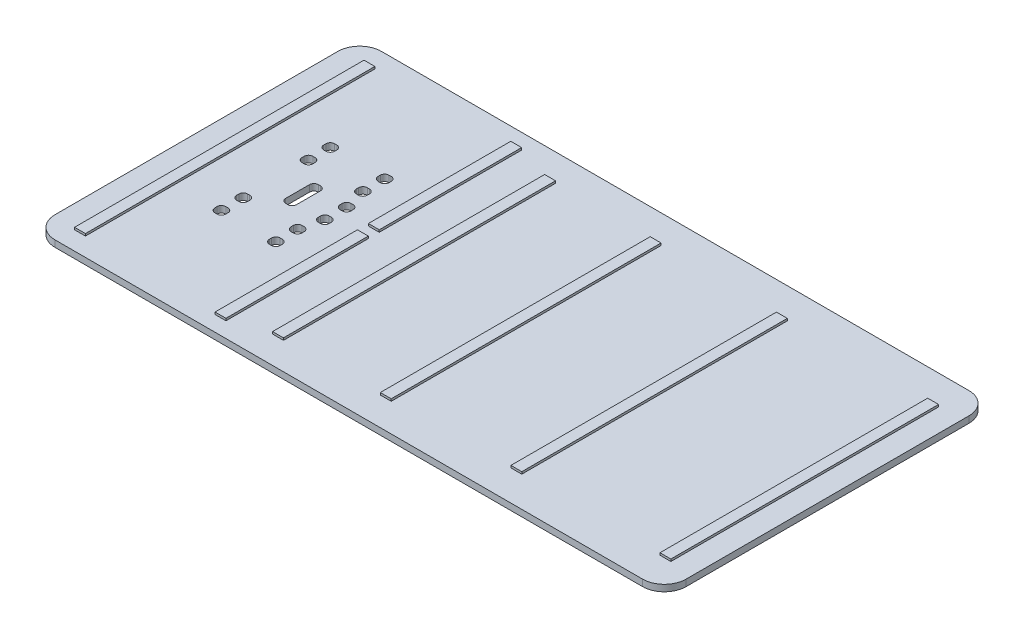
SolidWorks part; units mm, degrees
ref_plane "Front Plane" through (0, 0, 0) normal (0, 0, 1) x (1, 0, 0)
ref_plane "Top Plane" through (0, 0, 0) normal (0, 1, 0) x (1, 0, 0)
ref_plane "Right Plane" through (0, 0, 0) normal (1, 0, 0) x (0, 0, -1)
sketch "Sketch2" plane through (0, 0, 0) normal (0, 1, 0) x (1, 0, 0)
  line L0 (0, 0) -> (28541.0061, 0) construction
  line L1 (-66, 6.8479) -> (-66, -28534.1581) construction
  line L2 (-134.5, 66.5) -> (-129.5, 66.5)
  line L3 (-134.5, 66.5) -> (-134.5, -66.5)
  line L4 (-134.5, -66.5) -> (-129.5, -66.5)
  line L5 (-129.5, 66.5) -> (-129.5, -66.5)
  line L6 (-134.5, 66.5) -> (-129.5, -66.5) construction
  line L7 (-134.5, -66.5) -> (-129.5, 66.5) construction
  line L8 (-68.5, -67.935) -> (-63.5, -2.5) construction
  line L9 (-68.5, 67.935) -> (-63.5, 67.935)
  line L10 (-68.5, 67.935) -> (-68.5, 2.5)
  line L11 (-68.5, 2.5) -> (-63.5, 2.5)
  line L12 (-63.5, 67.935) -> (-63.5, 2.5)
  line L13 (-68.5, 67.935) -> (-63.5, 2.5) construction
  line L14 (-68.5, 2.5) -> (-63.5, 67.935) construction
  line L15 (-68.5, -2.5) -> (-63.5, -67.935) construction
  line L16 (-68.5, -67.935) -> (-68.5, -2.5)
  line L17 (-68.5, -2.5) -> (-63.5, -2.5)
  line L18 (-63.5, -67.935) -> (-63.5, -2.5)
  line L19 (-68.5, -67.935) -> (-63.5, -67.935)
  line L20 (-132, 0) -> (-132, -50000) construction
  line L21 (-47.5, 62.5) -> (-42.5, 62.5)
  line L22 (-47.5, 62.5) -> (-47.5, -62.5)
  line L23 (-47.5, -62.5) -> (-42.5, -62.5)
  line L24 (-42.5, 62.5) -> (-42.5, -62.5)
  line L25 (-47.5, 62.5) -> (-42.5, -62.5) construction
  line L26 (-47.5, -62.5) -> (-42.5, 62.5) construction
  line L27 (1.5, 62) -> (6.5, 62)
  line L28 (1.5, 62) -> (1.5, -62)
  line L29 (1.5, -62) -> (6.5, -62)
  line L30 (6.5, 62) -> (6.5, -62)
  line L31 (1.5, 62) -> (6.5, -62) construction
  line L32 (1.5, -62) -> (6.5, 62) construction
  line L33 (129.5, 61.5) -> (134.5, 61.5)
  line L34 (129.5, 61.5) -> (129.5, -61.5)
  line L35 (129.5, -61.5) -> (134.5, -61.5)
  line L36 (134.5, 61.5) -> (134.5, -61.5)
  line L37 (129.5, 61.5) -> (134.5, -61.5) construction
  line L38 (129.5, -61.5) -> (134.5, 61.5) construction
  line L39 (60.5, 61) -> (65.5, 61)
  line L40 (60.5, 61) -> (60.5, -61)
  line L41 (60.5, -61) -> (65.5, -61)
  line L42 (65.5, 61) -> (65.5, -61)
  line L43 (60.5, 61) -> (65.5, -61) construction
  line L44 (60.5, -61) -> (65.5, 61) construction
  line L45 (-45, 0) -> (-45, -50000) construction
  line L46 (4, 0) -> (4, -50000) construction
  line L47 (132, 0) -> (132, -50000) construction
  line L48 (63, 0) -> (63, -50000) construction
  line L49 (-132, 66.5) -> (132, 66.5) construction
  line L50 (0, 0) -> (0, -50000) construction
  point P3 (-132, 0)
  point P10 (-66, 35.2175)
  point P19 (-45, 0)
  point P24 (4, 0)
  point P29 (132, 0)
  point P34 (63, 0)
  dimension "D14" = 132
extrude "ElementGeometry" add sketch "Sketch2" along normal blind 1 from surface at 0 starting at plane "Top Plane"
sketch "Sketch5" plane through (0, 0, 0) normal (0, 1, 0) x (1, 0, 0)
  line L1 (-145, 75) -> (145, 75)
  line L2 (-145, 75) -> (-145, -75)
  line L3 (-145, -75) -> (145, -75)
  line L4 (145, 75) -> (145, -75)
  line L5 (-145, 75) -> (145, -75) construction
  line L6 (-145, -75) -> (145, 75) construction
  point P0 (0, 0)
  dimension "D1" = 290
  dimension "D2" = 150
extrude "BoardGeometry" add sketch "Sketch5" against normal blind 3 from surface at 0 starting at plane "Top Plane"
sketch "Sketch7" plane through (0, 0, 0) normal (0, 1, 0) x (1, 0, 0)
  line L0 (0, 0) -> (-50000, 0) construction
  line L1 (-81, 5) -> (-81, -5) construction
  line L2 (-83.5, 2.5) -> (-78.5, 7.5) construction
  line L3 (-83.5, -2.5) -> (-78.5, -2.5)
  line L4 (-83.5, -2.5) -> (-83.5, -7.5)
  line L5 (-83.5, -7.5) -> (-78.5, -7.5)
  line L6 (-78.5, -2.5) -> (-78.5, -7.5)
  line L7 (-83.5, -2.5) -> (-78.5, -7.5) construction
  line L8 (-83.5, -7.5) -> (-78.5, -2.5) construction
  line L9 (-83.5, 7.5) -> (-78.5, 2.5) construction
  line L10 (-83.5, 2.5) -> (-83.5, 7.5)
  line L11 (-83.5, 7.5) -> (-78.5, 7.5)
  line L12 (-78.5, 2.5) -> (-78.5, 7.5)
  line L13 (-83.5, 2.5) -> (-78.5, 2.5)
  line L14 (-66, 2.5) -> (-66, -2.5) construction
  line L15 (-63.5, 2.5) -> (-68.5, 2.5) construction
  line L16 (-68.5, -2.5) -> (-63.5, -2.5) construction
  line L17 (-68.5, -67.935) -> (-68.5, -2.5) construction
  line L19 (-98.5, 7.5) -> (-93.5, 7.5)
  line L20 (-98.5, 7.5) -> (-98.5, -7.5)
  line L21 (-98.5, -7.5) -> (-93.5, -7.5)
  line L22 (-93.5, 7.5) -> (-93.5, -7.5)
  line L23 (-98.5, 7.5) -> (-93.5, -7.5) construction
  line L24 (-98.5, -7.5) -> (-93.5, 7.5) construction
  point P3 (-66, 0)
  point P14 (-81, 0)
  point P24 (-96, 0)
  dimension "D1" = 5
  dimension "D2" = 5
  dimension "D3" = 5
  dimension "D4" = 10
  dimension "D5" = 10
extrude "CableCutout" cut sketch "Sketch7" against normal up to next
sketch "Sketch8" plane through (0, 0, 0) normal (0, 1, 0) x (1, 0, 0)
  line L0 (-98.5, 7.5) -> (-93.5, -7.5) construction
  line L1 (-93.5, 7.5) -> (-98.5, -7.5) construction
  line L2 (-93.5, 7.5) -> (-98.5, 7.5) construction
  line L3 (-98.5, -7.5) -> (-93.5, -7.5) construction
  line L4 (-98.5, 7.5) -> (-98.5, -7.5) construction
  line L5 (-93.5, -7.5) -> (-93.5, 7.5) construction
  line L6 (-96, -2.0682) -> (-96, -50002.0682) construction
  line L7 (-108.5, 15) -> (-83.5, 15) construction
  line L8 (-111, 17.5) -> (-106, 17.5)
  line L9 (-111, 17.5) -> (-111, 12.5)
  line L10 (-111, 12.5) -> (-106, 12.5)
  line L11 (-106, 17.5) -> (-106, 12.5)
  line L12 (-111, 17.5) -> (-106, 12.5) construction
  line L13 (-111, 12.5) -> (-106, 17.5) construction
  line L14 (0, 0) -> (50000, 0) construction
  line L15 (-81, 17.5) -> (-86, 12.5) construction
  line L16 (-81, 12.5) -> (-86, 17.5) construction
  line L17 (-81, 17.5) -> (-81, 12.5)
  line L18 (-81, 12.5) -> (-86, 12.5)
  line L19 (-86, 17.5) -> (-86, 12.5)
  line L20 (-81, 17.5) -> (-86, 17.5)
  line L21 (-81, -12.5) -> (-86, -17.5) construction
  line L22 (-81, -17.5) -> (-86, -12.5) construction
  line L23 (-111, -12.5) -> (-106, -17.5) construction
  line L24 (-108.5, -15) -> (-83.5, -15) construction
  line L25 (-81, -17.5) -> (-81, -12.5)
  line L26 (-81, -12.5) -> (-86, -12.5)
  line L27 (-86, -17.5) -> (-86, -12.5)
  line L28 (-81, -17.5) -> (-86, -17.5)
  line L29 (-111, -17.5) -> (-111, -12.5)
  line L30 (-111, -12.5) -> (-106, -12.5)
  line L31 (-106, -17.5) -> (-106, -12.5)
  line L32 (-111, -17.5) -> (-106, -17.5)
  line L33 (-106, -12.5) -> (-111, -17.5) construction
  line L34 (-108.5, -15) -> (-108.5, -25) construction
  line L35 (-108.5, -25) -> (-83.5, -25) construction
  line L36 (-83.5, -25) -> (-83.5, -15) construction
  line L37 (-81, -27.5) -> (-86, -27.5)
  line L38 (-111, -22.5) -> (-106, -22.5)
  line L39 (-111, -22.5) -> (-111, -27.5)
  line L40 (-111, -27.5) -> (-106, -27.5)
  line L41 (-106, -22.5) -> (-106, -27.5)
  line L42 (-111, -22.5) -> (-106, -27.5) construction
  line L43 (-111, -27.5) -> (-106, -22.5) construction
  line L44 (-81, -22.5) -> (-81, -27.5)
  line L45 (-81, -27.5) -> (-86, -22.5) construction
  line L46 (-81, -22.5) -> (-86, -27.5) construction
  line L47 (-86, -22.5) -> (-86, -27.5)
  line L48 (-81, -22.5) -> (-86, -22.5)
  line L49 (-81, 27.5) -> (-86, 27.5)
  line L50 (-81, 22.5) -> (-81, 27.5)
  line L51 (-81, 27.5) -> (-86, 22.5) construction
  line L52 (-81, 22.5) -> (-86, 27.5) construction
  line L53 (-86, 22.5) -> (-86, 27.5)
  line L54 (-81, 22.5) -> (-86, 22.5)
  line L55 (-108.5, 25) -> (-83.5, 25) construction
  line L56 (-111, 22.5) -> (-106, 27.5) construction
  line L57 (-111, 27.5) -> (-106, 22.5) construction
  line L58 (-106, 22.5) -> (-106, 27.5)
  line L59 (-111, 27.5) -> (-106, 27.5)
  line L60 (-111, 22.5) -> (-111, 27.5)
  line L61 (-111, 22.5) -> (-106, 22.5)
  point P15 (-96, 0)
  point P17 (-108.5, 15)
  point P28 (-96, 15)
  dimension "D1" = 30
  dimension "D2" = 25
  dimension "D3" = 5
  dimension "D4" = 5
  dimension "D5" = 5
extrude "MountingHoles" cut sketch "Sketch8" against normal through all both and the other way through all
fillet "BoardFillet" radius 10 4 edges at (-145, -1.5, -75) (-145, -1.5, 75) (145, -1.5, -75) (145, -1.5, 75)
fillet "MountingHoleFillet" radius 2 44 edges at (-78.5, -1.5, 7.5) (-83.5, -1.5, 7.5) (-83.5, -1.5, 2.5) (-78.5, -1.5, 2.5) (-83.5, -1.5, -2.5) (-83.5, -1.5, -7.5) (-78.5, -1.5, -7.5) (-78.5, -1.5, -2.5) (-93.5, -1.5, 7.5) (-98.5, -1.5, 7.5) (-98.5, -1.5, -7.5) (-93.5, -1.5, -7.5) (-106, -1.5, -12.5) (-111, -1.5, -12.5) (-111, -1.5, -17.5) (-106, -1.5, -17.5) (-111, -1.5, -22.5) (-111, -1.5, -27.5) (-106, -1.5, -27.5) (-106, -1.5, -22.5) (-81, -1.5, -22.5) (-86, -1.5, -22.5) (-86, -1.5, -27.5) (-81, -1.5, -27.5) (-81, -1.5, 27.5) (-86, -1.5, 27.5) (-86, -1.5, 22.5) (-81, -1.5, 22.5) (-81, -1.5, -17.5) (-81, -1.5, -12.5) (-86, -1.5, -12.5) (-86, -1.5, -17.5) (-106, -1.5, 27.5) (-111, -1.5, 27.5) (-106, -1.5, 22.5) (-81, -1.5, 12.5) (-81, -1.5, 17.5) (-86, -1.5, 17.5) (-86, -1.5, 12.5) (-111, -1.5, 22.5) (-106, -1.5, 12.5) (-106, -1.5, 17.5) (-111, -1.5, 17.5) (-111, -1.5, 12.5)
equation "\"ElementWidth\"= 5mm'Antenna element width"
equation "\"ReflectorLength\"= 133mm'Reflector length"
equation "\"DipolePosition\"= 66mm'Dipole position"
equation "\"DipoleLegLength\"= 65.435mm'HalfwaveDipoleLegLength"
equation "\"DirectorPosition1\"= 87mm'Director Position 1 "
equation "\"DirectorLength1\"= 125mm'Director Length 1 "
equation "\"DirectorPosition2\"= 136mm'Director Position 2"
equation "\"DirectorLength2\"= 124mm'Director Length 2 "
equation "\"DirectorPosition3\"= 195mm'Director Position 3 "
equation "\"DirectorLength3\"= 123mm'Director Length 3"
equation "\"DirectorPosition4\"= 264mm'Director Position 4 "
equation "\"DirectorLength4\"= 122'DirectorLength 4"
equation "\"D1@Sketch2\"=\"ReflectorLength\""
equation "\"DipoleSpacing\"= 5mm'Dipole Element Spacing"
equation "\"D2@Sketch2\"=\"DipoleSpacing\""
equation "\"D3@Sketch2\"=\"DipoleLegLength\""
equation "\"D4@Sketch2\"=\"DirectorLength1\""
equation "\"D5@Sketch2\"=\"DirectorLength2\""
equation "\"D6@Sketch2\"=\"DirectorLength3\""
equation "\"D7@Sketch2\"=\"DirectorLength4\""
equation "\"D8@Sketch2\"=\"DipolePosition\""
equation "\"D10@Sketch2\"=\"DirectorPosition1\""
equation "\"D11@Sketch2\"=\"DirectorPosition2\""
equation "\"D12@Sketch2\"=\"DirectorPosition3\""
equation "\"D13@Sketch2\"=\"DirectorPosition4\""
equation "\"ElementThickness\"= 1mm'Copper Element Thiccness"
equation "\"FR4Thickness\"= 3mm'FR4 Substrate Thickness"
equation "\"D1@ElementGeometry\" = \"ElementThickness\""
equation "\"D1@BoardGeometry\" = \"FR4Thickness\""
